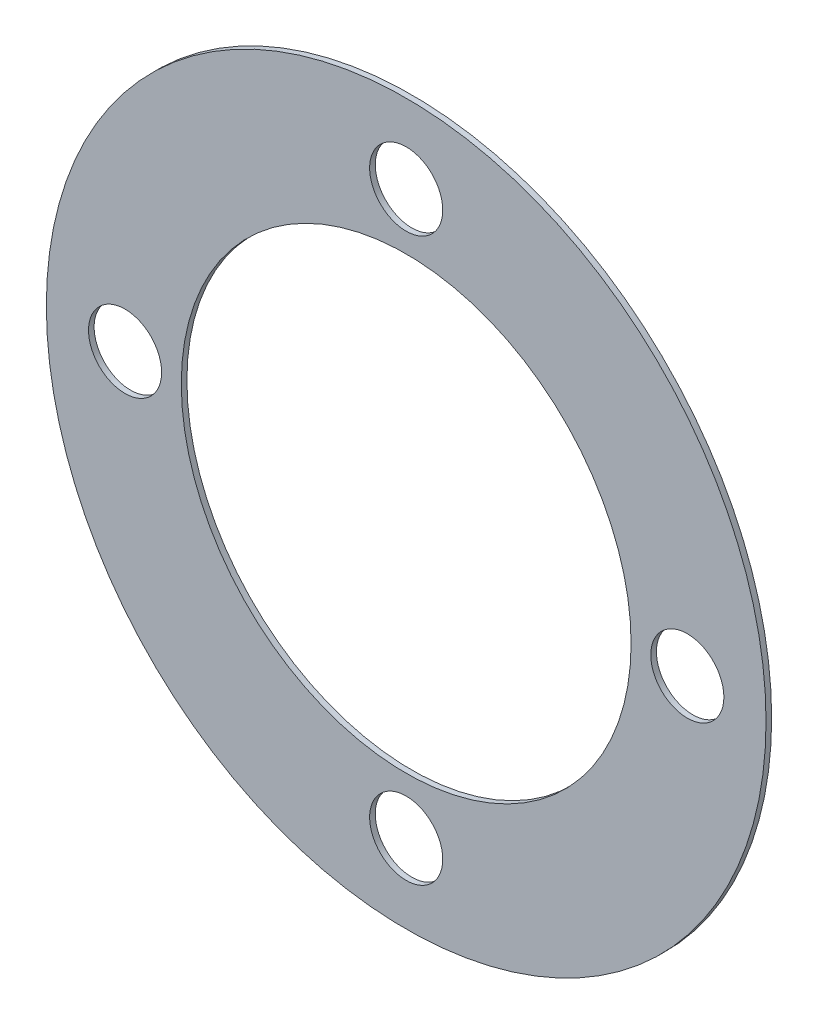
SolidWorks part; units mm, degrees
ref_plane "Front Plane" through (0, 0, 0) normal (0, 0, 1) x (1, 0, 0)
ref_plane "Top Plane" through (0, 0, 0) normal (0, 1, 0) x (1, 0, 0)
ref_plane "Right Plane" through (0, 0, 0) normal (1, 0, 0) x (0, 0, -1)
sketch "Sketch1" plane through (0, 0, 0) normal (0, 0, 1) x (1, 0, 0)
  circle A0 centre (0, 0) radius 32
  circle A1 centre (0, 0) radius 20
  circle A2 centre (0, 0) radius 25 construction
  circle A3 centre (0, 25) radius 3.25
  circle A4 centre (25, 0) radius 3.25
  circle A5 centre (0, -25) radius 3.25
  circle A6 centre (-25, 0) radius 3.25
  point P16 (0, 0)
  dimension "D1" = 64
  dimension "D2" = 40
  dimension "D3" = 50
  dimension "D4" = 6.5
  dimension "D5" = 4
extrude "Boss-Extrude1" add sketch "Sketch1" along normal blind 0.5
